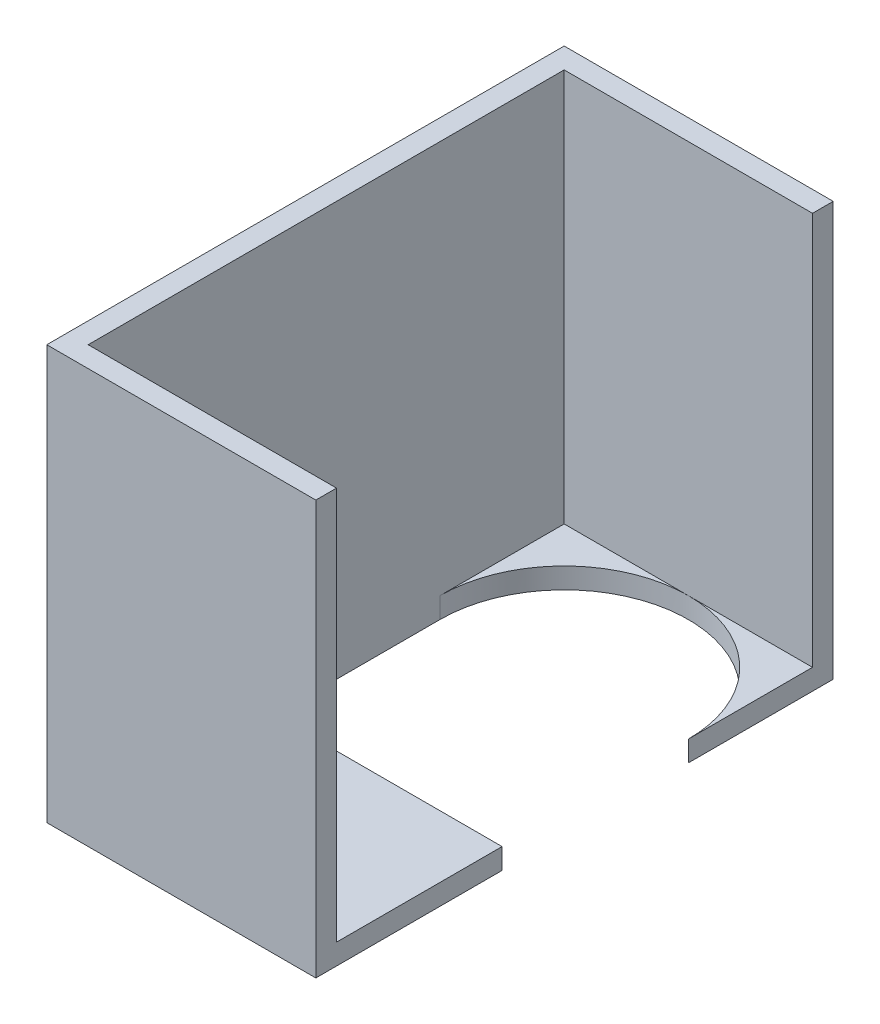
SolidWorks part; units mm, degrees
ref_plane "정면" through (0, 0, 0) normal (0, 0, 1) x (1, 0, 0)
ref_plane "윗면" through (0, 0, 0) normal (0, 1, 0) x (1, 0, 0)
ref_plane "우측면" through (0, 0, 0) normal (1, 0, 0) x (0, 0, -1)
sketch "스케치15" plane through (0, 0, 0) normal (0, 1, 0) x (1, 0, 0)
  line L1 (-6, -12.5) -> (7, -12.5)
  line L2 (-6, -12.5) -> (-6, 12.5)
  line L3 (-6, 12.5) -> (7, 12.5)
  line L4 (7, -12.5) -> (7, 12.5)
  dimension "D1" = 13
  dimension "D2" = 25
extrude "보스-돌출4" add sketch "스케치15" along normal blind 20
sketch "스케치16" plane through (0, 0, 0) normal (0, 1, 0) x (1, 0, 0)
  line L1 (-5, 11.5) -> (7, 11.5)
  line L2 (-5, 11.5) -> (-5, -11.5)
  line L3 (-5, -11.5) -> (7, -11.5)
  line L4 (7, 11.5) -> (7, -11.5)
  line L5 (-6, -12.5) -> (7, -12.5) construction
  line L7 (7, -12.5) -> (7, 12.5) construction
  dimension "D1" = 12
  dimension "D2" = 23
  dimension "D3" = 1
extrude "컷-돌출47" cut sketch "스케치16" along normal through all from offset 1
sketch "스케치17" plane through (0, 0, 0) normal (0, 1, 0) x (1, 0, 0)
  line L0 (7, 11.5) -> (-5, 11.5) construction
  line L1 (7, -11.5) -> (7, 11.5) construction
  line L3 (-5, -3.5) -> (7, -3.5)
  line L4 (-5, -3.5) -> (-5, 5.5)
  line L6 (7, -3.5) -> (7, 5.5)
  arc A0 (7, 5.5) -> (-5, 5.5) centre (1, 5.5) ccw
  dimension "D1" = 12
  dimension "D2" = 12
  dimension "D3" = 9
extrude "컷-돌출48" cut sketch "스케치17" along normal through all
